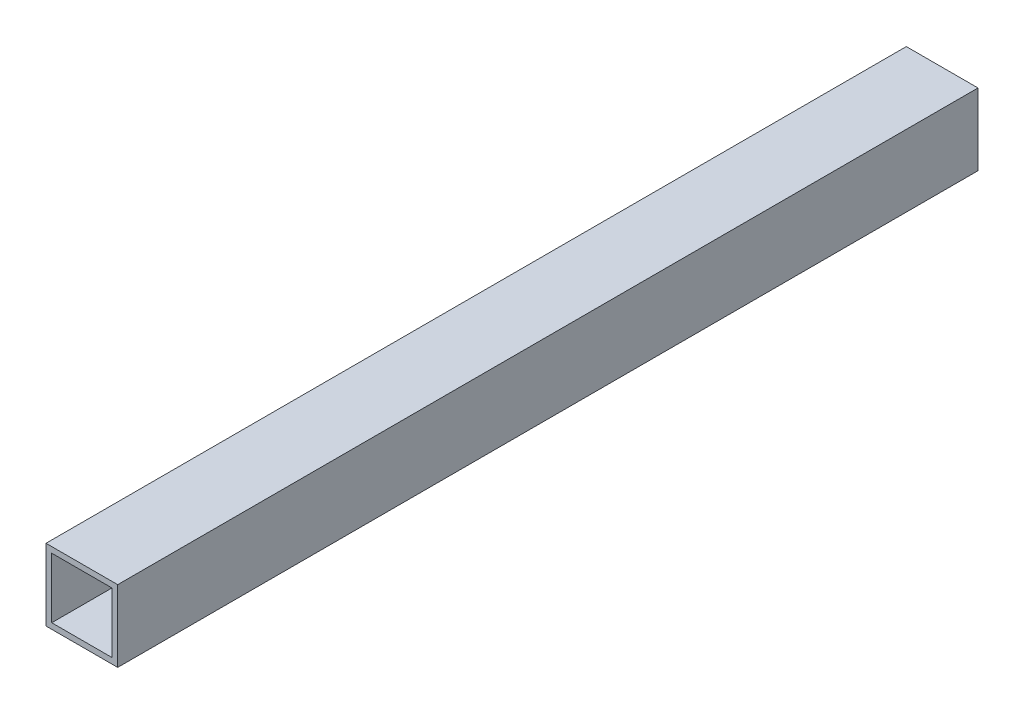
SolidWorks part; units mm, degrees
ref_plane "Front Plane" through (0, 0, 0) normal (0, 0, 1) x (1, 0, 0)
ref_plane "Top Plane" through (0, 0, 0) normal (0, 1, 0) x (1, 0, 0)
ref_plane "Right Plane" through (0, 0, 0) normal (1, 0, 0) x (0, 0, -1)
sketch "Sketch1" plane through (0, 0, 0) normal (0, 0, 1) x (1, 0, 0)
  line L1 (-12.5, -12.5) -> (12.5, -12.5)
  line L2 (-12.5, -12.5) -> (-12.5, 12.5)
  line L3 (-12.5, 12.5) -> (12.5, 12.5)
  line L4 (12.5, -12.5) -> (12.5, 12.5)
  line L5 (-12.5, -12.5) -> (12.5, 12.5) construction
  line L6 (-12.5, 12.5) -> (12.5, -12.5) construction
  line L7 (-10.5, 10.5) -> (10.5, 10.5)
  line L8 (-10.5, 10.5) -> (-10.5, -10.5)
  line L9 (-10.5, -10.5) -> (10.5, -10.5)
  line L10 (10.5, 10.5) -> (10.5, -10.5)
  line L11 (-10.5, 10.5) -> (10.5, -10.5) construction
  line L12 (-10.5, -10.5) -> (10.5, 10.5) construction
  point P0 (0, 0)
  point P6 (0, 0)
  dimension "D1" = 25
  dimension "D2" = 25
  dimension "D3" = 2
extrude "Boss-Extrude1" add sketch "Sketch1" along normal blind 300
